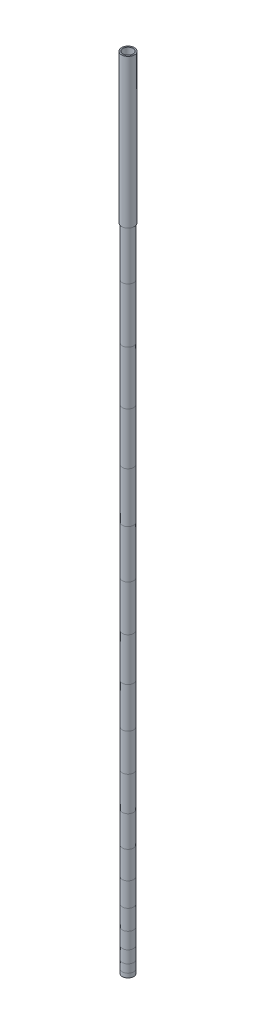
SolidWorks part; units mm, degrees
ref_plane "Piano frontale" through (0, 0, 0) normal (0, 0, 1) x (1, 0, 0)
ref_plane "Piano superiore" through (0, 0, 0) normal (0, 1, 0) x (1, 0, 0)
ref_plane "Piano destro" through (0, 0, 0) normal (1, 0, 0) x (0, 0, -1)
sketch "Schizzo1" plane through (0, 0, 0) normal (0, 1, 0) x (1, 0, 0)
  circle A0 centre (0, 0) radius 8
  circle A1 centre (0, 0) radius 7
  dimension "D1" = 14
  dimension "D2" = 16
extrude "Estrusione-Estrusione1" add sketch "Schizzo1" along normal blind 5.8
ref_plane "Piano1" through (0, 5.8, 0) normal (0, 1, 0) x (1, 0, 0)
ref_plane "Piano2" through (0, 17.2, 0) normal (0, 1, 0) x (1, 0, 0)
ref_plane "Piano3" through (0, 34.4, 0) normal (0, 1, 0) x (1, 0, 0)
ref_plane "Piano4" through (0, 57.1, 0) normal (0, 1, 0) x (1, 0, 0)
ref_plane "Piano5" through (0, 85.2, 0) normal (0, 1, 0) x (1, 0, 0)
ref_plane "Piano6" through (0, 118.7, 0) normal (0, 1, 0) x (1, 0, 0)
ref_plane "Piano7" through (0, 157.3, 0) normal (0, 1, 0) x (1, 0, 0)
ref_plane "Piano8" through (0, 200.8, 0) normal (0, 1, 0) x (1, 0, 0)
ref_plane "Piano9" through (0, 249.1, 0) normal (0, 1, 0) x (1, 0, 0)
ref_plane "Piano10" through (0, 301.8, 0) normal (0, 1, 0) x (1, 0, 0)
ref_plane "Piano11" through (0, 358.8, 0) normal (0, 1, 0) x (1, 0, 0)
ref_plane "Piano12" through (0, 419.6, 0) normal (0, 1, 0) x (1, 0, 0)
ref_plane "Piano13" through (0, 484.1, 0) normal (0, 1, 0) x (1, 0, 0)
ref_plane "Piano14" through (0, 551.9, 0) normal (0, 1, 0) x (1, 0, 0)
ref_plane "Piano15" through (0, 622.6, 0) normal (0, 1, 0) x (1, 0, 0)
ref_plane "Piano16" through (0, 695.8, 0) normal (0, 1, 0) x (1, 0, 0)
ref_plane "Piano17" through (0, 771.3, 0) normal (0, 1, 0) x (1, 0, 0)
ref_plane "Piano18" through (0, 848.6, 0) normal (0, 1, 0) x (1, 0, 0)
ref_plane "Piano19" through (0, 927.3, 0) normal (0, 1, 0) x (1, 0, 0)
ref_plane "Piano20" through (0, 1007, 0) normal (0, 1, 0) x (1, 0, 0)
ref_plane "Piano21" through (0, 1087.3, 0) normal (0, 1, 0) x (1, 0, 0)
ref_plane "Piano22" through (0, 1127.6, 0) normal (0, 1, 0) x (1, 0, 0)
sketch "Schizzo3" plane through (0, 5.8, 0) normal (0, 1, 0) x (1, 0, 0)
  circle A0 centre (0, 0) radius 8
  circle A1 centre (0, 0) radius 7
  dimension "D1" = 14
  dimension "D2" = 16
sketch "Schizzo4" plane through (0, 17.2, 0) normal (0, 1, 0) x (1, 0, 0)
  circle A0 centre (0, 0) radius 8
  circle A1 centre (0, 0) radius 7
  dimension "D1" = 14
  dimension "D2" = 16
sketch "Schizzo5" plane through (0, 34.4, 0) normal (0, 1, 0) x (1, 0, 0)
  circle A0 centre (0, 0) radius 8
  circle A1 centre (0, 0) radius 7
  dimension "D1" = 14
  dimension "D2" = 16
sketch "Schizzo6" plane through (0, 57.1, 0) normal (0, 1, 0) x (1, 0, 0)
  circle A0 centre (0, 0) radius 8
  circle A1 centre (0, 0) radius 7
  dimension "D1" = 14
  dimension "D2" = 16
sketch "Schizzo7" plane through (0, 85.2, 0) normal (0, 1, 0) x (1, 0, 0)
  circle A0 centre (0, 0) radius 8
  circle A1 centre (0, 0) radius 7
  dimension "D1" = 14
  dimension "D2" = 16
sketch "Schizzo8" plane through (0, 118.7, 0) normal (0, 1, 0) x (1, 0, 0)
  circle A0 centre (0, 0) radius 8
  circle A1 centre (0, 0) radius 7
  dimension "D1" = 14
  dimension "D2" = 16
sketch "Schizzo9" plane through (0, 157.3, 0) normal (0, 1, 0) x (1, 0, 0)
  circle A0 centre (0, 0) radius 8
  circle A1 centre (0, 0) radius 7
  dimension "D1" = 14
  dimension "D2" = 16
sketch "Schizzo10" plane through (0, 200.8, 0) normal (0, 1, 0) x (1, 0, 0)
  circle A0 centre (0, 0) radius 8
  circle A1 centre (0, 0) radius 7
  dimension "D1" = 14
  dimension "D2" = 16
sketch "Schizzo11" plane through (0, 249.1, 0) normal (0, 1, 0) x (1, 0, 0)
  circle A0 centre (0, 0) radius 8
  circle A1 centre (0, 0) radius 7
  dimension "D1" = 14
  dimension "D2" = 16
sketch "Schizzo12" plane through (0, 301.8, 0) normal (0, 1, 0) x (1, 0, 0)
  circle A0 centre (0, 0) radius 8
  circle A1 centre (0, 0) radius 7
  dimension "D1" = 14
  dimension "D2" = 16
sketch "Schizzo13" plane through (0, 358.8, 0) normal (0, 1, 0) x (1, 0, 0)
  circle A0 centre (0, 0) radius 8
  circle A1 centre (0, 0) radius 7
  dimension "D1" = 14
  dimension "D2" = 16
sketch "Schizzo14" plane through (0, 419.6, 0) normal (0, 1, 0) x (1, 0, 0)
  circle A0 centre (0, 0) radius 8
  circle A1 centre (0, 0) radius 7
  dimension "D1" = 14
  dimension "D2" = 16
sketch "Schizzo15" plane through (0, 484.1, 0) normal (0, 1, 0) x (1, 0, 0)
  circle A0 centre (0, 0) radius 8
  circle A1 centre (0, 0) radius 7
  dimension "D1" = 14
  dimension "D2" = 16
sketch "Schizzo16" plane through (0, 551.9, 0) normal (0, 1, 0) x (1, 0, 0)
  circle A0 centre (0, 0) radius 8
  circle A1 centre (0, 0) radius 7
  dimension "D1" = 14
  dimension "D2" = 16
sketch "Schizzo17" plane through (0, 622.6, 0) normal (0, 1, 0) x (1, 0, 0)
  circle A0 centre (0, 0) radius 8
  circle A1 centre (0, 0) radius 7
  dimension "D1" = 14
  dimension "D2" = 16
sketch "Schizzo18" plane through (0, 695.8, 0) normal (0, 1, 0) x (1, 0, 0)
  circle A0 centre (0, 0) radius 8
  circle A1 centre (0, 0) radius 7
  dimension "D1" = 14
  dimension "D2" = 16
sketch "Schizzo19" plane through (0, 771.3, 0) normal (0, 1, 0) x (1, 0, 0)
  circle A0 centre (0, 0) radius 8
  circle A1 centre (0, 0) radius 7
  dimension "D1" = 14
  dimension "D2" = 16
sketch "Schizzo20" plane through (0, 848.6, 0) normal (0, 1, 0) x (1, 0, 0)
  circle A0 centre (0, 0) radius 8
  circle A1 centre (0, 0) radius 7
  dimension "D1" = 14
  dimension "D2" = 16
sketch "Schizzo21" plane through (0, 927.3, 0) normal (0, 1, 0) x (1, 0, 0)
  circle A0 centre (0, 0) radius 8
  circle A1 centre (0, 0) radius 7
  dimension "D1" = 14
  dimension "D2" = 16
sketch "Schizzo22" plane through (0, 1007, 0) normal (0, 1, 0) x (1, 0, 0)
  circle A0 centre (0, 0) radius 8
  circle A1 centre (0, 0) radius 7
  dimension "D1" = 14
  dimension "D2" = 16
sketch "Schizzo23" plane through (0, 1087.3, 0) normal (0, 1, 0) x (1, 0, 0)
  circle A0 centre (0, 0) radius 8
  circle A1 centre (0, 0) radius 7
  dimension "D1" = 14
  dimension "D2" = 16
sketch "Schizzo24" plane through (0, 1127.6, 0) normal (0, 1, 0) x (1, 0, 0)
  circle A0 centre (0, 0) radius 8
  circle A1 centre (0, 0) radius 7
  dimension "D1" = 14
  dimension "D2" = 16
extrude "Estrusione-Estrusione2" add sketch "Schizzo3" along normal up to surface (11.4 mm away) separate body contours A0 up to plane "Piano2"
extrude "Estrusione-Estrusione3" add sketch "Schizzo4" along normal up to surface (17.2 mm away) separate body contours A0 up to plane "Piano3"
extrude "Estrusione-Estrusione4" add sketch "Schizzo5" along normal up to surface (22.7 mm away) separate body contours A0 up to plane "Piano4"
extrude "Estrusione-Estrusione5" add sketch "Schizzo6" along normal up to surface (28.1 mm away) separate body contours A0 up to plane "Piano5"
extrude "Estrusione-Estrusione6" add sketch "Schizzo7" along normal up to surface (33.5 mm away) separate body contours A0 up to plane "Piano6"
extrude "Estrusione-Estrusione7" add sketch "Schizzo8" along normal up to surface (38.6 mm away) separate body contours A0 up to plane "Piano7"
extrude "Estrusione-Estrusione8" add sketch "Schizzo9" along normal up to surface (43.5 mm away) separate body contours A0 up to plane "Piano8"
extrude "Estrusione-Estrusione9" add sketch "Schizzo10" along normal up to surface (48.3 mm away) separate body contours A0 up to plane "Piano9"
extrude "Estrusione-Estrusione10" add sketch "Schizzo11" along normal up to surface (52.7 mm away) separate body contours A0 up to plane "Piano10"
extrude "Estrusione-Estrusione11" add sketch "Schizzo12" along normal up to surface (57 mm away) separate body contours A0 up to plane "Piano11"
extrude "Estrusione-Estrusione12" add sketch "Schizzo13" along normal up to surface (60.8 mm away) separate body contours A0 up to plane "Piano12"
extrude "Estrusione-Estrusione13" add sketch "Schizzo14" along normal up to surface (64.5 mm away) separate body contours A0 up to plane "Piano13"
extrude "Estrusione-Estrusione14" add sketch "Schizzo15" along normal up to surface (67.8 mm away) separate body contours A0 up to plane "Piano14"
extrude "Estrusione-Estrusione15" add sketch "Schizzo16" along normal up to surface (70.7 mm away) separate body contours A0 up to plane "Piano15"
extrude "Estrusione-Estrusione16" add sketch "Schizzo17" along normal up to surface (73.2 mm away) separate body contours A0 up to plane "Piano16"
extrude "Estrusione-Estrusione17" add sketch "Schizzo18" along normal up to surface (75.5 mm away) separate body contours A0 up to plane "Piano17"
extrude "Estrusione-Estrusione18" add sketch "Schizzo19" along normal up to surface (77.3 mm away) separate body contours A0 up to plane "Piano18"
extrude "Estrusione-Estrusione19" add sketch "Schizzo20" along normal up to surface (78.7 mm away) separate body contours A0 up to plane "Piano19"
extrude "Estrusione-Estrusione20" add sketch "Schizzo21" along normal up to surface (79.7 mm away) separate body contours A0 up to plane "Piano20"
extrude "Estrusione-Estrusione21" add sketch "Schizzo22" along normal up to surface (80.3 mm away) separate body contours A0 up to plane "Piano21"
extrude "Estrusione-Estrusione22" add sketch "Schizzo23" along normal up to surface (40.3 mm away) separate body contours A0 up to plane "Piano22"
extrude "Taglio-Estrusione1" cut sketch "Schizzo24" against normal through all contours A1
sketch "Schizzo25" plane through (0, 1127.6, 0) normal (0, 1, 0) x (1, 0, 0)
  circle A0 centre (0, 0) radius 9
  circle A1 centre (0, 0) radius 8
  dimension "D1" = 18
  dimension "D2" = 16
extrude "Estrusione-Estrusione23" add sketch "Schizzo25" against normal blind 210 separate body
